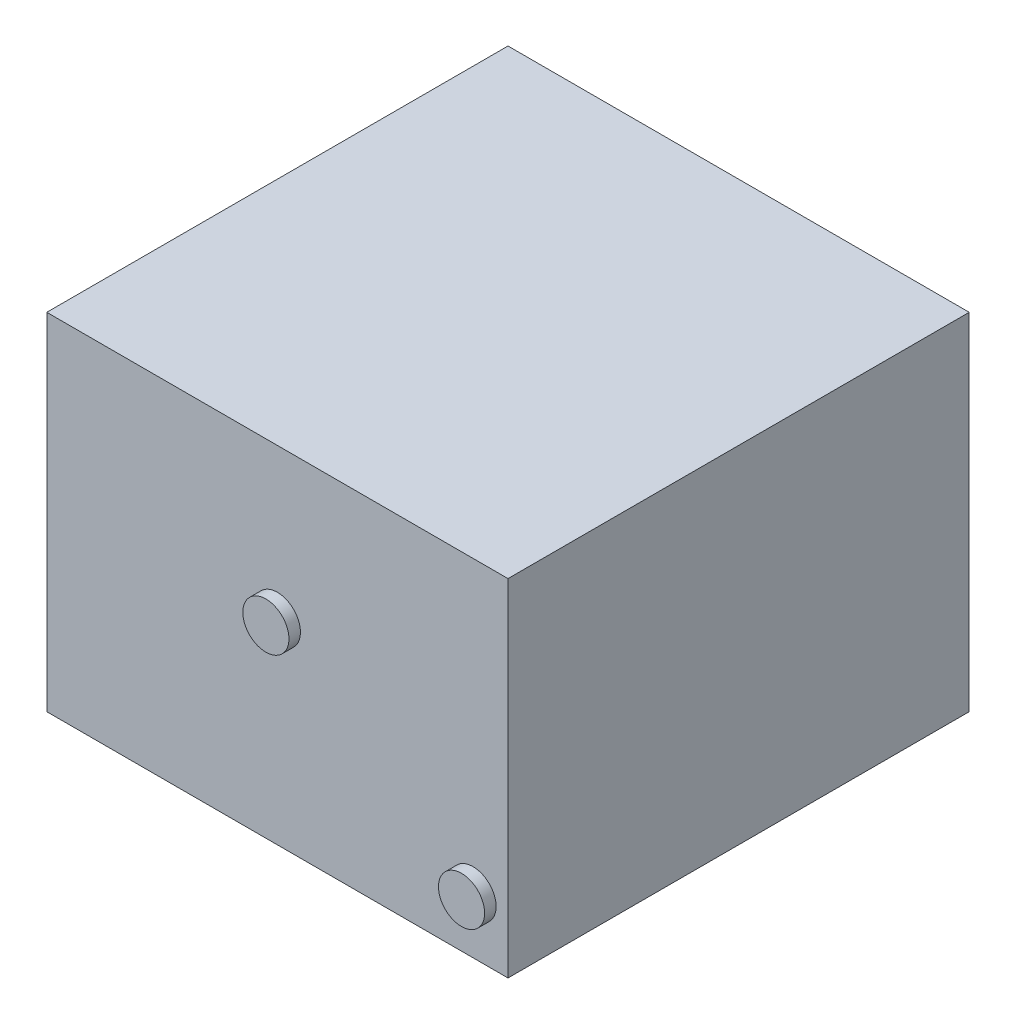
SolidWorks part; units mm, degrees
ref_plane "前视基准面" through (0, 0, 0) normal (0, 0, 1) x (1, 0, 0)
ref_plane "上视基准面" through (0, 0, 0) normal (0, 1, 0) x (1, 0, 0)
ref_plane "右视基准面" through (0, 0, 0) normal (1, 0, 0) x (0, 0, -1)
sketch "草图1" plane through (0, 0, 0) normal (0, 0, 1) x (1, 0, 0)
  line L1 (-100, -75) -> (100, -75)
  line L2 (-100, -75) -> (-100, 75)
  line L3 (-100, 75) -> (100, 75)
  line L4 (100, -75) -> (100, 75)
  line L5 (-100, -75) -> (100, 75) construction
  line L6 (-100, 75) -> (100, -75) construction
  point P0 (0, 0)
  dimension "D1" = 150
  dimension "D2" = 200
extrude "凸台-拉伸1" add sketch "草图1" along normal mid plane 200
sketch "草图2" plane through (0, 0, 100) normal (0, 0, 1) x (1, 0, 0)
  line L0 (0, -75) -> (0, 75) construction
  line L1 (-100, -75) -> (100, -75) construction
  line L2 (100, 75) -> (-100, 75) construction
  line L3 (0, 9.8528) -> (84.8528, -75) construction
  line L4 (60.6092, -50.7563) -> (84.8528, -50.7563) construction
  line L5 (84.8528, -50.7563) -> (84.8528, -75) construction
  circle A0 centre (0, 9.8528) radius 10
  circle A1 centre (84.8528, -50.7563) radius 10
  point P11 (60.6092, -50.7563)
  point P12 (0, 0)
  dimension "D1" = 45
  dimension "D5" = 20
  dimension "D2" = 20
  dimension "D3" = 120
  dimension "D4" = 85.7143
extrude "凸台-拉伸2" add sketch "草图2" along normal blind 5
mirror "镜向1" about plane through (0, 0, 0) normal (0, 0, 1) of "凸台-拉伸2"
